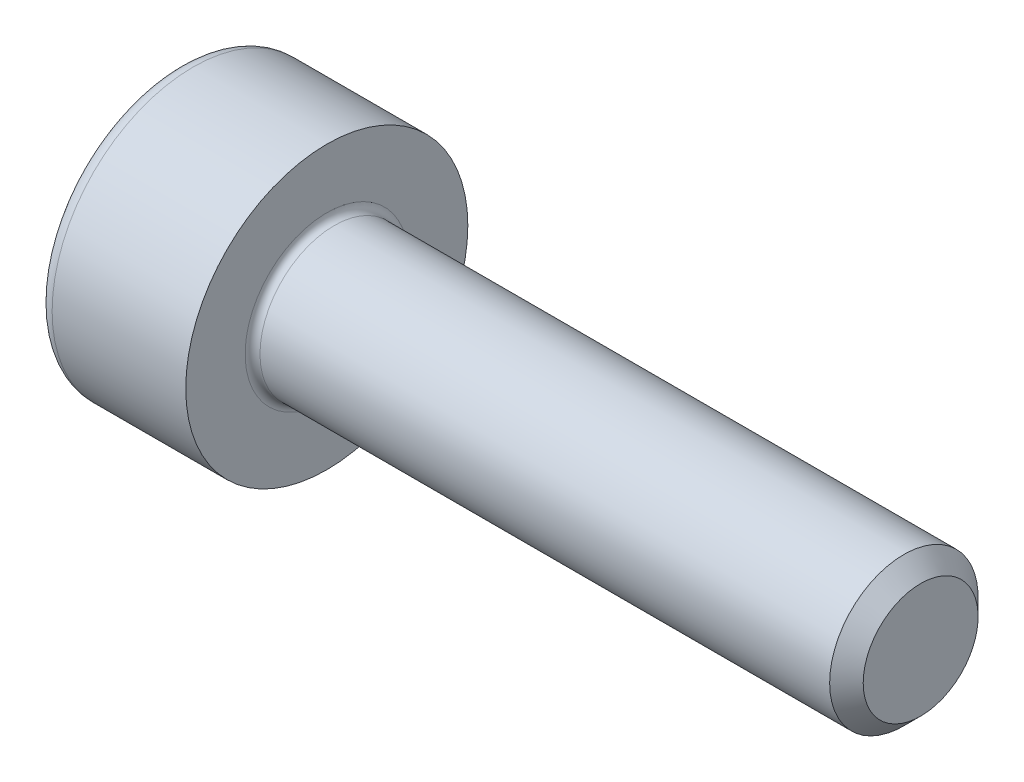
SolidWorks part; units mm, degrees
revolve "Base-Revolve" add sketch "BodySke"
sketch "BodySke" plane through (0, 0, 0) normal (0, 0, 1) x (1, 0, 0)
  line L0 (0, 0) -> (0, 1.9)
  line L1 (0, 1.9) -> (2, 1.9)
  line L2 (2, 1.9) -> (2, 1)
  line L3 (2, 1) -> (9.774, 1)
  line L4 (10, 0.774) -> (10, 0)
  line L5 (10, 0) -> (0, 0)
  line L6 (-31.75, 0) -> (127, 0) construction
  line L8 (10, 0.774) -> (9.774, 1)
  line L10 (10, -0.774) -> (9.774, -1) construction
  line L11 (2.4, 9.525) -> (2.4, 3.175) construction
  line L12 (-8, 9.525) -> (-8, 3.175) construction
  line L13 (-50, 9.525) -> (-50, 3.175) construction
  dimension "Head_ht" = 2
  dimension "Length" = 8
  dimension "Body_ch_ang" = 45
  dimension "Diameter" = 2
  dimension "Minor_dia" = 1.548
  dimension "Advance" = 0.4
  dimension "Thread_nom" = 18
  dimension "Thread_length" = 60
  dimension "Head_dia" = 3.8
cosmetic thread "ThreadCosmetic" [suppressed]
fillet "Fillet1" radius 0.1 1 edges at (2, 0, 1)
fillet "Fillet2" radius 0.2 1 edges at (0, 0, 1.9)
ref_plane "Plane1" through (0, 0, 0) normal (0, 0, 1) x (1, 0, 0)
ref_plane "Plane2" through (0, 0, 0) normal (0, 1, 0) x (1, 0, 0)
ref_plane "Plane3" through (0, 0, 0) normal (1, 0, 0) x (0, 0, -1)
sketch "Sketch2" plane through (0, 0, 0) normal (0, 0, 1) x (1, 0, 0)
  line L0 (0, 0.76) -> (1, 0.76)
  line L1 (1, 0.76) -> (1.4388, 0)
  line L2 (-31.75, 0) -> (127, 0) construction
  line L3 (1.4388, 0) -> (0, 0)
  line L4 (0, 0) -> (0, 0.76)
  line L6 (0, 0) -> (47.625, 0) construction
  dimension "D1" = 0.76
  dimension "D2" = 60
  dimension "Depth" = 1
revolve "Hex-PreBroach" cut sketch "Sketch2" angle 360 about L6
sketch "Sketch3" plane through (0, 0, 0) normal (-1, 0, 0) x (0, 0.5, 0.866)
  line L0 (0.4388, 0.76) -> (-0.4388, 0.76)
  line L1 (-0.4388, 0.76) -> (-0.8776, 0)
  line L2 (0.4388, 0.76) -> (0.8776, 0)
  line L3 (0.4388, -0.76) -> (0.8776, 0)
  line L4 (0.4388, -0.76) -> (-0.4388, -0.76)
  line L5 (-0.4388, -0.76) -> (-0.8776, 0)
  dimension "D1" = 0.76
  dimension "D2" = 0.76
  dimension "Hex_size" = 1.52
extrude "Hex" cut sketch "Sketch3" against normal blind 1
sketch "ThdSchSke" plane through (0, 0, 0) normal (0, 0, 1) x (1, 0, 0)
  line L0 (3.2, -0.774) -> (3.0418, -1)
  line L1 (3.2, -0.774) -> (3.3582, -1)
  line L2 (3.3582, -1) -> (3.3582, -1.25)
  line L3 (-3.175, 0) -> (5.1513, 0) construction
  line L4 (0, 1.7) -> (0, -1.7) construction
  line L5 (3.3582, -1.25) -> (3.0418, -1.25)
  line L6 (3.0418, -1.25) -> (3.0418, -1)
  dimension "Thread_minor" = 1.548
  dimension "Diameter" = 2
  dimension "Start" = 3.2
revolve "ThreadSchematic" [suppressed] cut sketch "ThdSchSke" angle 360 about L3
pattern_linear "ThdSchPat" [suppressed]
equation "\"D2@Sketch3\" = \"Hex_size@Sketch3\" / 2"
equation "\"D1@Sketch3\" = \"Hex_size@Sketch3\" / 2"
equation "\"D1@Sketch2\" = \"Hex_size@Sketch3\" / 2"
equation "\"Thread_minor@ThreadCosmetic\"  =  \"Minor_dia@BodySke\""
equation "\"Depth@Sketch2\" =  \"Key_eng@Hex\""
equation "\"Thread_length@ThreadCosmetic\" = ((sgn( (\"Length@BodySke\" - \"Advance@BodySke\" * 3.0) - \"Thread_nom@BodySke\" )-1)*( (\"Length@BodySke\" - \"Advance@BodySke\" * 3.0) - \"Thread_nom@BodySke\" ))/-2+ \"Thread_nom@BodySke\""
equation "\"Thread_minor@ThdSchSke\" = \"Minor_dia@BodySke\""
equation "\"Diameter@ThdSchSke\" = \"Diameter@BodySke\""
equation "\"Overcut@ThdSchSke\" = \"Diameter@BodySke\" * 1.25"
equation "\"Start@ThdSchSke\" = \"Head_ht@BodySke\" + \"Length@BodySke\" - \"Thread_length@ThreadCosmetic\"  '---Non-countersunk---"
equation "\"Num_threads@ThdSchPat\" = int( \"Thread_length@ThreadCosmetic\" / \"Advance@BodySke\" + 0.999 )  + 1"
equation "\"Advance@ThdSchPat\" = \"Thread_length@ThreadCosmetic\" /  (\"Num_threads@ThdSchPat\" - 1) 'relax it"
equation "\"Num_threads@ThdSchPat\" = \"Num_threads@ThdSchPat\" - sgn( \"Num_threads@ThdSchPat\" - 1) '---chamfered tips only---"
